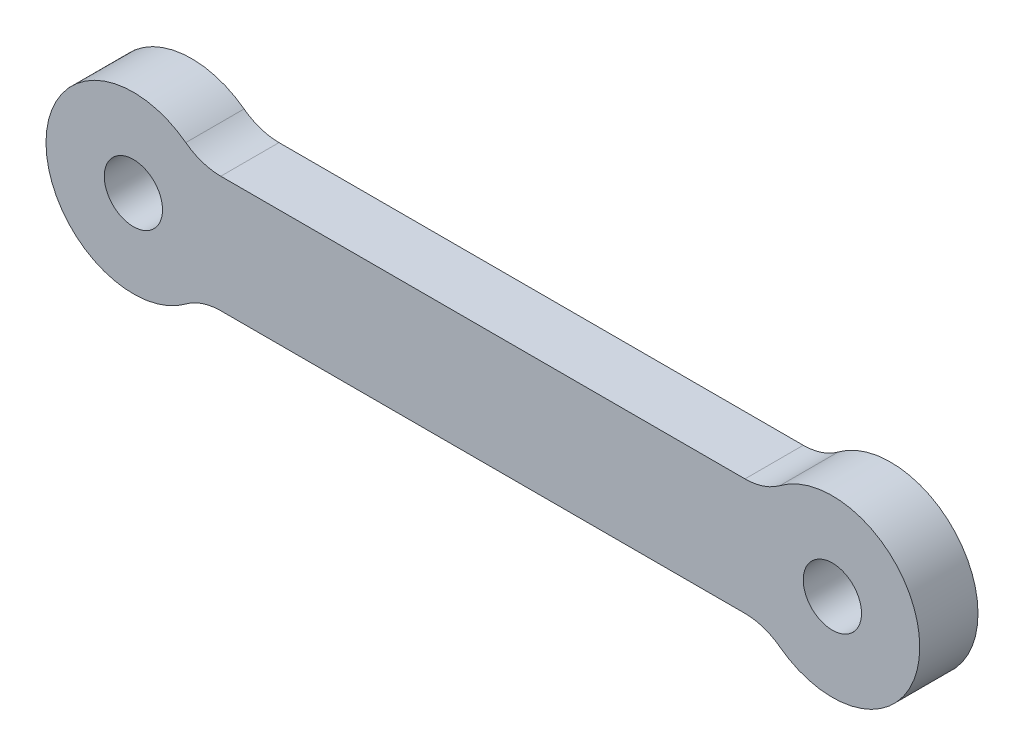
SolidWorks part; units mm, degrees
ref_plane "Front Plane" through (0, 0, 0) normal (0, 0, 1) x (1, 0, 0)
ref_plane "Top Plane" through (0, 0, 0) normal (0, 1, 0) x (1, 0, 0)
ref_plane "Right Plane" through (0, 0, 0) normal (1, 0, 0) x (0, 0, -1)
sketch "Sketch1" plane through (0, 0, 0) normal (0, 0, 1) x (1, 0, 0)
  line L0 (-76.2, 0) -> (0, 0) construction
  line L1 (-66.675, 6.35) -> (-9.525, 6.35)
  line L2 (-9.525, -6.35) -> (-66.675, -6.35)
  arc A0 (-5.715, -7.62) -> (-5.715, 7.62) centre (0, 0) ccw
  arc A1 (-70.485, 7.62) -> (-70.485, -7.62) centre (-76.2, 0) ccw
  arc A2 (-66.675, -6.35) -> (-70.485, -7.62) centre (-66.675, -12.7) ccw
  arc A3 (-9.525, -6.35) -> (-5.715, -7.62) centre (-9.525, -12.7) cw
  arc A4 (-9.525, 6.35) -> (-5.715, 7.62) centre (-9.525, 12.7) ccw
  arc A5 (-66.675, 6.35) -> (-70.485, 7.62) centre (-66.675, 12.7) cw
  circle A6 centre (-76.2, 0) radius 3.175
  circle A7 centre (0, 0) radius 3.175
  dimension "D1" = 19.05
  dimension "D4" = 6.35
  dimension "D5" = 6.35
  dimension "D2" = 76.2
  dimension "D3" = 12.7
extrude "Boss-Extrude1" add sketch "Sketch1" along normal mid plane 6.35
